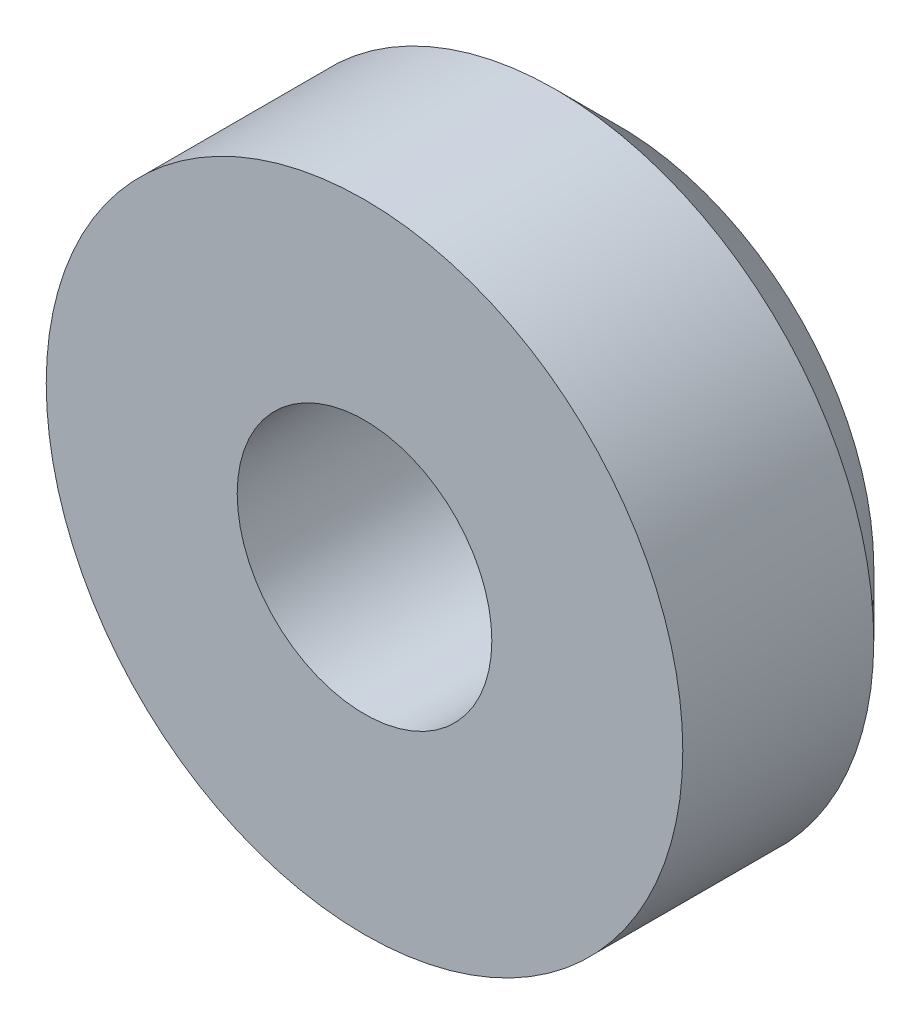
SolidWorks part; units mm, degrees
ref_plane "前视基准面" through (0, 0, 0) normal (0, 0, 1) x (1, 0, 0)
ref_plane "上视基准面" through (0, 0, 0) normal (0, 1, 0) x (1, 0, 0)
ref_plane "右视基准面" through (0, 0, 0) normal (1, 0, 0) x (0, 0, -1)
sketch "草图1" plane through (0, 0, 0) normal (0, 0, 1) x (1, 0, 0)
  circle A0 centre (0, 0) radius 15
  dimension "D1" = 30
extrude "凸台-拉伸1" add sketch "草图1" along normal blind 2
sketch "草图2" plane through (0, 0, 2) normal (0, 0, 1) x (1, 0, 0)
  circle A0 centre (0, 0) radius 15
  circle A1 centre (0, 0) radius 6
  dimension "D1" = 12
  dimension "D2" = 30
extrude "凸台-拉伸2" add sketch "草图2" along normal blind 10
chamfer "倒角1" distance 3 angle 45 1 edges at (15, 0, 0)
